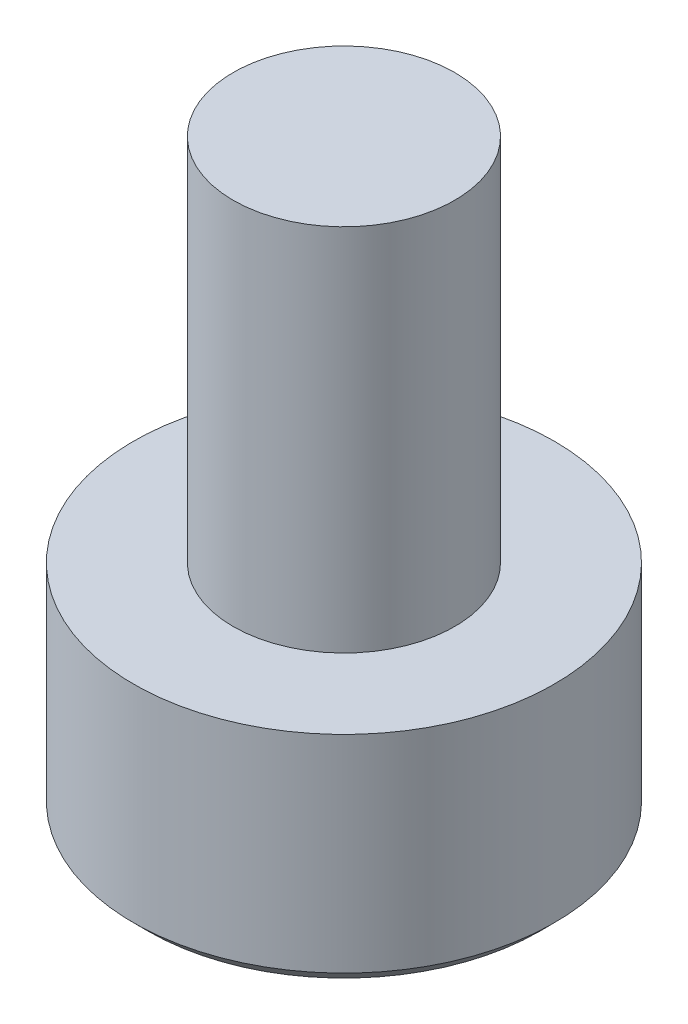
SolidWorks part; units mm, degrees
ref_plane "前视基准面" through (0, 0, 0) normal (0, 0, 1) x (1, 0, 0)
ref_plane "上视基准面" through (0, 0, 0) normal (0, 1, 0) x (1, 0, 0)
ref_plane "右视基准面" through (0, 0, 0) normal (1, 0, 0) x (0, 0, -1)
other "Configuration Table"
sketch "草图1" plane through (0, 0, 0) normal (0, 1, 0) x (1, 0, 0)
  circle A0 centre (0, 0) radius 1.5
  dimension "D1" = 3
extrude "凸台-拉伸1" add sketch "草图1" along normal blind 5
sketch "草图2" plane through (0, 0, 0) normal (0, -1, 0) x (1, 0, 0)
  circle A0 centre (0, 0) radius 2.85
  dimension "D1" = 5.7
extrude "凸台-拉伸2" add sketch "草图2" along normal blind 3
sketch "草图3" plane through (0, -3, 0) normal (0, -1, 0) x (1, 0, 0)
  line L1 (1.4434, 0) -> (0.7217, 1.25)
  line L2 (0.7217, 1.25) -> (-0.7217, 1.25)
  line L3 (-0.7217, 1.25) -> (-1.4434, 0)
  line L4 (-1.4434, 0) -> (-0.7217, -1.25)
  line L5 (-0.7217, -1.25) -> (0.7217, -1.25)
  line L6 (0.7217, -1.25) -> (1.4434, 0)
  circle A0 centre (0, 0) radius 1.25 construction
  dimension "D1" = 2.5
extrude "切除-拉伸1" cut sketch "草图3" against normal blind 1
chamfer "倒角1" distance 0.2 angle 45 1 edges at (0, -3, -2.85)
